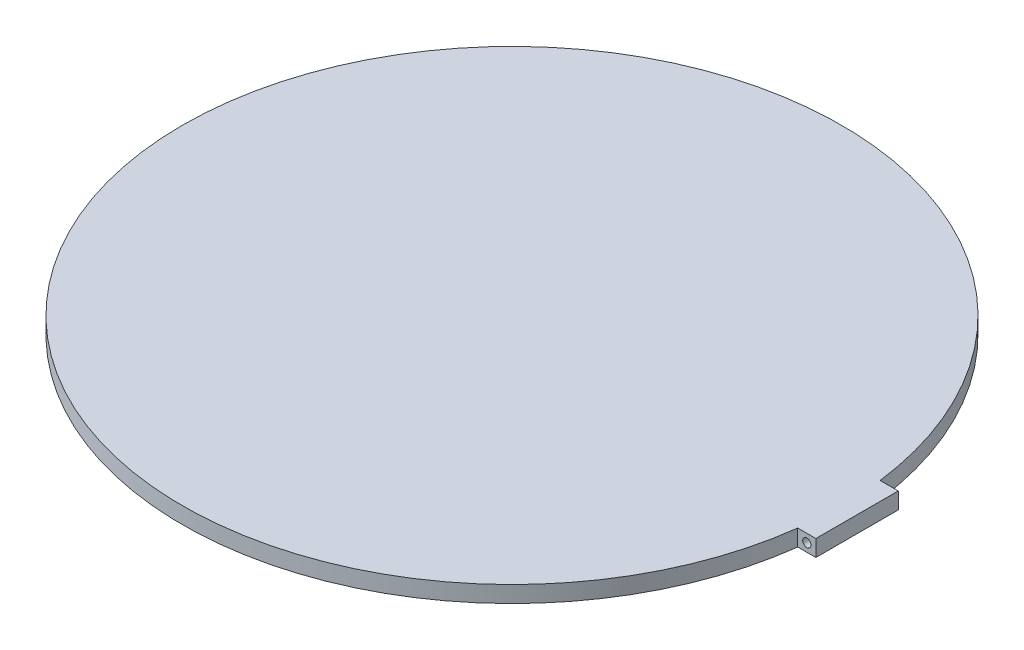
SolidWorks part; units mm, degrees
ref_plane "Front Plane" through (0, 0, 0) normal (0, 0, 1) x (1, 0, 0)
ref_plane "Top Plane" through (0, 0, 0) normal (0, 1, 0) x (1, 0, 0)
ref_plane "Right Plane" through (0, 0, 0) normal (1, 0, 0) x (0, 0, -1)
sketch "Sketch1" plane through (0, 0, 0) normal (0, 1, 0) x (1, 0, 0)
  line L0 (0, 0) -> (0, 12.7)
  line L1 (0, 12.7) -> (-2.794, 12.7)
  line L2 (0, 0) -> (-2.794, 0)
  arc A0 (-2.794, 0) -> (-2.794, 12.7) centre (-53.1956, 6.35) cw
  dimension "D1" = 50.8
  dimension "D2" = 2.794
  dimension "D3" = 12.7
  dimension "D4" = 2.794
extrude "Boss-Extrude1" add sketch "Sketch1" along normal blind 2.54
sketch "Sketch2" plane through (0, 0, 0) normal (0, 0, 1) x (1, 0, 0)
  line L0 (-2.794, 0) -> (0, 2.54) construction
  line L1 (0, 2.54) -> (0, 0) construction
  line L2 (-2.794, 2.54) -> (0, 0) construction
  circle A0 centre (-1.397, 1.27) radius 0.635
  dimension "D1" = 1.27
extrude "Cut-Extrude1" cut sketch "Sketch2" against normal through all
